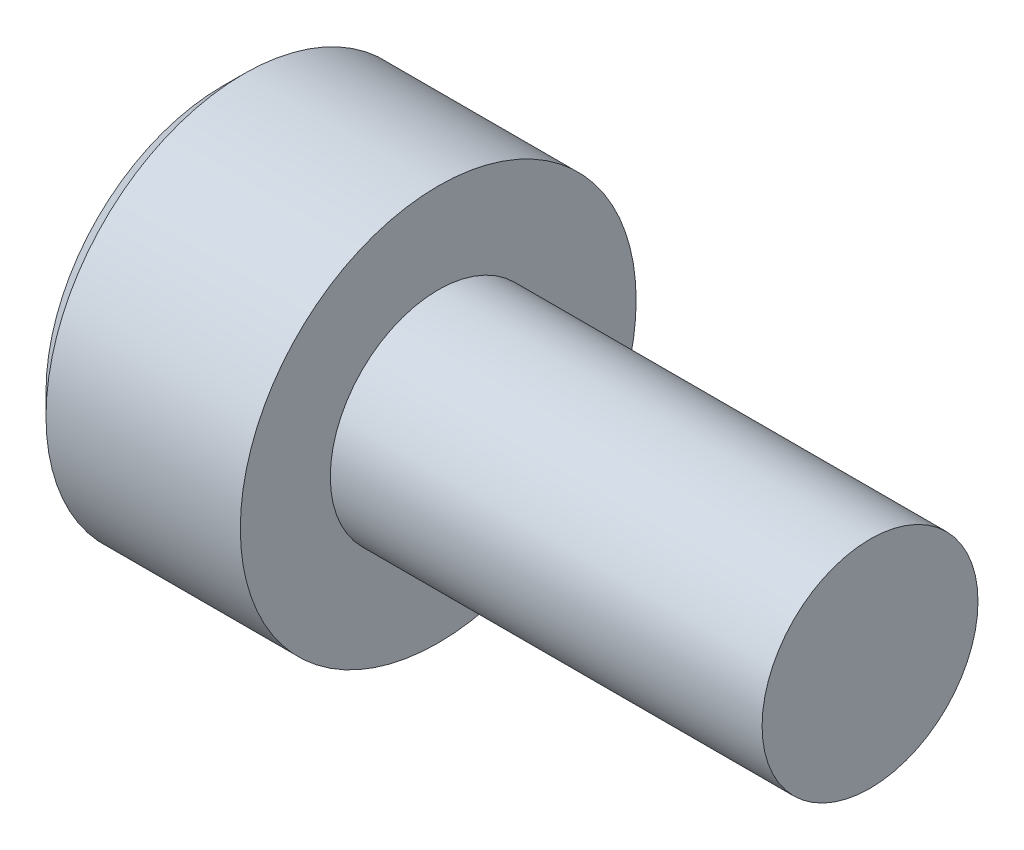
SolidWorks part; units mm, degrees
material "SUS304相当"
ref_plane "Front Plane" through (0, 0, 0) normal (0, 0, 1) x (1, 0, 0)
ref_plane "Top Plane" through (0, 0, 0) normal (0, 1, 0) x (1, 0, 0)
ref_plane "Right Plane" through (0, 0, 0) normal (1, 0, 0) x (0, 0, -1)
sketch "Sketch1" plane through (0, 0, 0) normal (0, 0, 1) x (1, 0, 0)
  line L0 (-3, 0) -> (6, 0) construction
  line L1 (0, 1.5) -> (6, 1.5)
  line L3 (-3, 0) -> (6, 0)
  line L4 (6, 1.5) -> (6, 0)
  line L6 (0, 1.5) -> (0, 2.75)
  line L7 (0, 2.75) -> (-3, 2.75)
  line L8 (-3, 0) -> (-3, 2.75)
  dimension "L" = 6
  dimension "M" = 3
  dimension "E" = 3
  dimension "A" = 5.5
revolve "Revolve1" add sketch "Sketch1" about L0
cosmetic thread "Thread1" parameters "L_s"=6, "ATD"=2.459
sketch "Sketch2" plane through (0, 0, 0) normal (0, 0, 1) x (1, 0, 0)
  line L0 (-3, 0) -> (-0.9489, 0) construction
  line L1 (-3, 0) -> (6, 0) construction
  line L2 (-0.9489, 0) -> (-1.7, 1.25)
  line L3 (-1.7, 1.25) -> (-3, 1.25)
  line L4 (-3, 0) -> (-3, 2.75) construction
  line L5 (-3, 1.25) -> (-3, 0)
  line L6 (-3, 0) -> (-0.9489, 0)
  dimension "MSM_1" = 1.3
  dimension "FIX_2" = 59
revolve "Cut-Revolve1" cut sketch "Sketch2" about L0
sketch "Sketch3" plane through (-3, 0, 0) normal (-1, 0, 0) x (0, 0, 1)
  line L0 (0, -3.025) -> (0, 3.025) construction
  line L1 (1.25, 0.7217) -> (0, 1.4434)
  line L2 (0, 1.4434) -> (-1.25, 0.7217)
  line L3 (-1.25, 0.7217) -> (-1.25, -0.7217)
  line L4 (-1.25, -0.7217) -> (0, -1.4434)
  line L5 (0, -1.4434) -> (1.25, -0.7217)
  line L6 (1.25, -0.7217) -> (1.25, 0.7217)
  circle A0 centre (0, 0) radius 1.25 construction
extrude "Cut-Extrude1" cut sketch "Sketch3" against normal blind 1.3
chamfer "Chamfer1" distance 0.3 1 edges at (-3, -2.75, 0)
